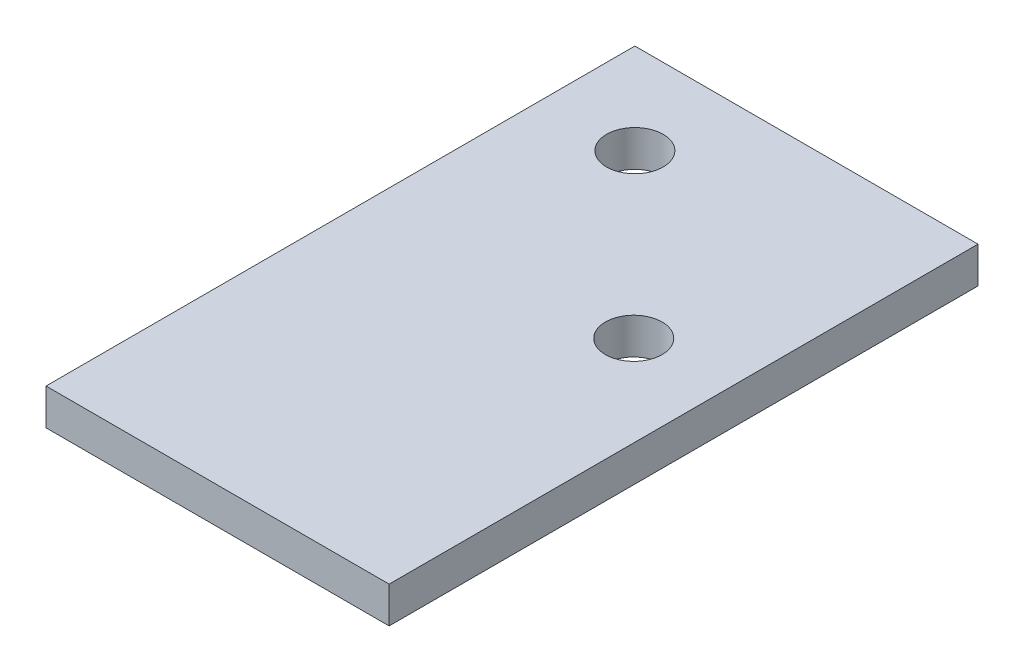
SolidWorks part; units mm, degrees
material "1.2316 (X36CrMo17)"
ref_plane "Front Plane" through (0, 0, 0) normal (0, 0, 1) x (1, 0, 0)
ref_plane "Top Plane" through (0, 0, 0) normal (0, 1, 0) x (1, 0, 0)
ref_plane "Right Plane" through (0, 0, 0) normal (1, 0, 0) x (0, 0, -1)
sketch "Sketch1" plane through (0, 0, 0) normal (0, 1, 0) x (1, 0, 0)
  line L1 (-15.15, 26) -> (15.15, 26)
  line L2 (-15.15, 26) -> (-15.15, -26)
  line L3 (-15.15, -26) -> (15.15, -26)
  line L4 (15.15, 26) -> (15.15, -26)
  line L5 (-15.15, 26) -> (15.15, -26) construction
  line L6 (-15.15, -26) -> (15.15, 26) construction
  point P0 (0, 0)
  dimension "D1" = 30.3
  dimension "D2" = 52
extrude "Boss-Extrude1" add sketch "Sketch1" against normal blind 3.2
sketch "Sketch2" plane through (0, 0, 0) normal (0, 1, 0) x (1, 0, 0)
  line L0 (15.15, -26) -> (15.15, 26) construction
  line L1 (15.15, 26) -> (-15.15, 26) construction
  line L2 (-15.15, 26) -> (-15.15, -26) construction
  point P0 (-7.15, 18)
  point P2 (7.15, 3.6)
  dimension "D1" = 8
  dimension "D2" = 8
  dimension "D3" = 8
  dimension "D4" = 22.4
hole_wizard "M6 Tapped Hole1" positions "Sketch2" profile "Sketch3" tap size "M6" standard "ISO" end condition through all
cosmetic thread "Hole Thread1"
cosmetic thread "Hole Thread2"
sketch "Sketch3" plane through (-7.15, 0, -18) normal (1, 0, 0) x (0, 0, 1)
  line L0 (0, 0) -> (0, 3.2)
  line L1 (0, 3.2) -> (2.5, 3.2)
  line L2 (2.5, 3.2) -> (2.5, 0)
  line L5 (2.5, 0) -> (0, 0)
  line L11 (0, -6.35) -> (0, 107.95) construction
  dimension "Thru Tap Drill Dia." = 5
  dimension "Thru Tap Drill Depth" = 3.2
